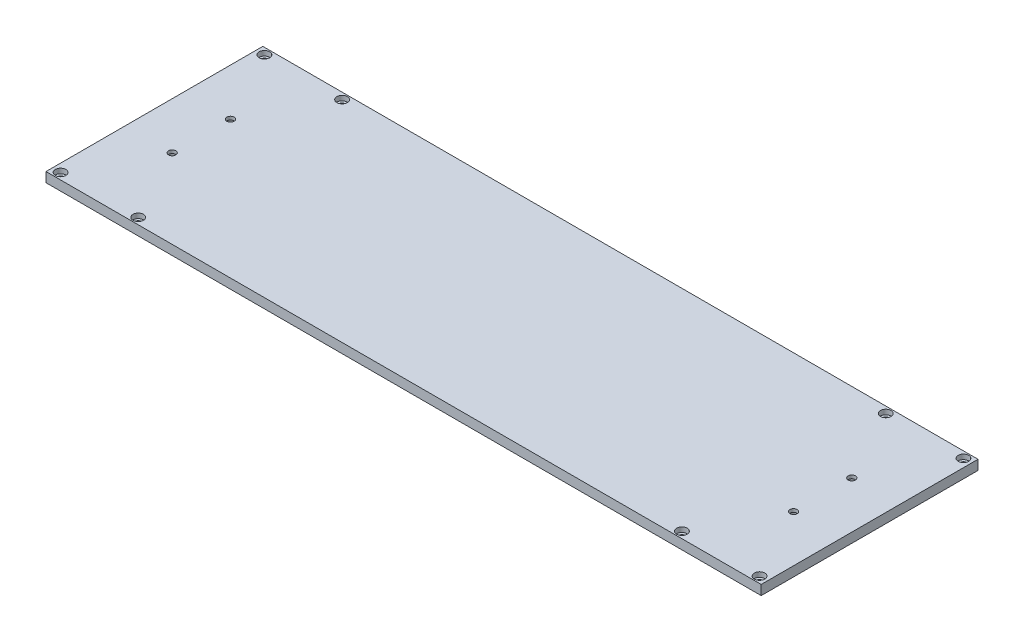
SolidWorks part; units mm, degrees
ref_plane "Front Plane" through (0, 0, 0) normal (0, 0, 1) x (1, 0, 0)
ref_plane "Top Plane" through (0, 0, 0) normal (0, 1, 0) x (1, 0, 0)
ref_plane "Right Plane" through (0, 0, 0) normal (1, 0, 0) x (0, 0, -1)
sketch "Sketch1" plane through (0, 0, 0) normal (0, 1, 0) x (1, 0, 0)
  line L1 (-221, 67) -> (221, 67)
  line L2 (-221, 67) -> (-221, -67)
  line L3 (-221, -67) -> (221, -67)
  line L4 (221, 67) -> (221, -67)
  line L5 (-221, 67) -> (221, -67) construction
  line L6 (-221, -67) -> (221, 67) construction
  point P0 (0, 0)
  dimension "D1" = 134
  dimension "D2" = 442
extrude "Boss-Extrude1" add sketch "Sketch1" along normal blind 6
hole_wizard "CBORE for M3 SHCS2" positions "Sketch4" profile "Sketch3" counterbore size "M3" standard "ANSI Metric"
sketch "Sketch4" plane through (0, 6, 0) normal (0, 1, 0) x (1, 0, 0)
  line L0 (216, -63) -> (216, 63) construction
  line L1 (216, 63) -> (168, 63) construction
  line L2 (168, 63) -> (168, -63) construction
  line L3 (168, -63) -> (216, -63) construction
  line L6 (221, -67) -> (221, 67) construction
  point P0 (216, 63)
  point P2 (168, 63)
  point P4 (168, -63)
  point P6 (216, -63)
  point P20 (216, 0)
  point P23 (221, 0)
  dimension "D1" = 48
  dimension "D2" = 126
  dimension "D3" = 5
sketch "Sketch3" plane through (216, 6, -63) normal (1, 0, 0) x (0, 0, 1)
  line L0 (0, 0) -> (0, 18.4015)
  line L1 (0, 18.4015) -> (1.7, 17.38)
  line L2 (1.7, 17.38) -> (1.7, 3)
  line L3 (1.7, 3) -> (3.25, 3)
  line L4 (3.25, 3) -> (3.25, 0)
  line L5 (3.25, 0) -> (0, 0)
  line L10 (0, 18.4015) -> (-1.7, 17.38) construction
  line L11 (0, -6.35) -> (0, 107.95) construction
  dimension "Hole Dia." = 3.4
  dimension "Hole Depth" = 17.38
  dimension "C'Bore Dia." = 6.5
  dimension "C'Bore Depth" = 3
  dimension "Drill Angle" = 118
hole_wizard "CBORE for M4 SHCS1" positions "Sketch5" profile "Sketch6" counterbore size "M4" standard "ANSI Metric"
sketch "Sketch5" plane through (0, 0, 0) normal (0, -1, 0) x (-1, 0, 0)
  line L8 (-168, -63) -> (-216, -63) construction
  line L9 (-192, 18) -> (-192, -18) construction
  point P39 (-192, -63)
  point P41 (-192, 18)
  point P43 (-192, -18)
  point P51 (-192, 0)
  dimension "D1" = 36
sketch "Sketch6" plane through (192, 0, 18) normal (1, 0, 0) x (0, 0, -1)
  line L0 (0, 0) -> (0, 11.3519)
  line L1 (0, 11.3519) -> (2.25, 10)
  line L2 (2.25, 10) -> (2.25, 4)
  line L3 (2.25, 4) -> (4, 4)
  line L4 (4, 4) -> (4, 0)
  line L5 (4, 0) -> (0, 0)
  line L10 (0, 11.3519) -> (-2.25, 10) construction
  line L11 (0, -6.35) -> (0, 107.95) construction
  dimension "Hole Dia." = 4.5
  dimension "Hole Depth" = 10
  dimension "C'Bore Dia." = 8
  dimension "C'Bore Depth" = 4
  dimension "Drill Angle" = 118
pattern_linear "LPattern1" count 2 spacing 384 along (-1, 0, 0) of "CBORE for M3 SHCS2", "CBORE for M4 SHCS1"
